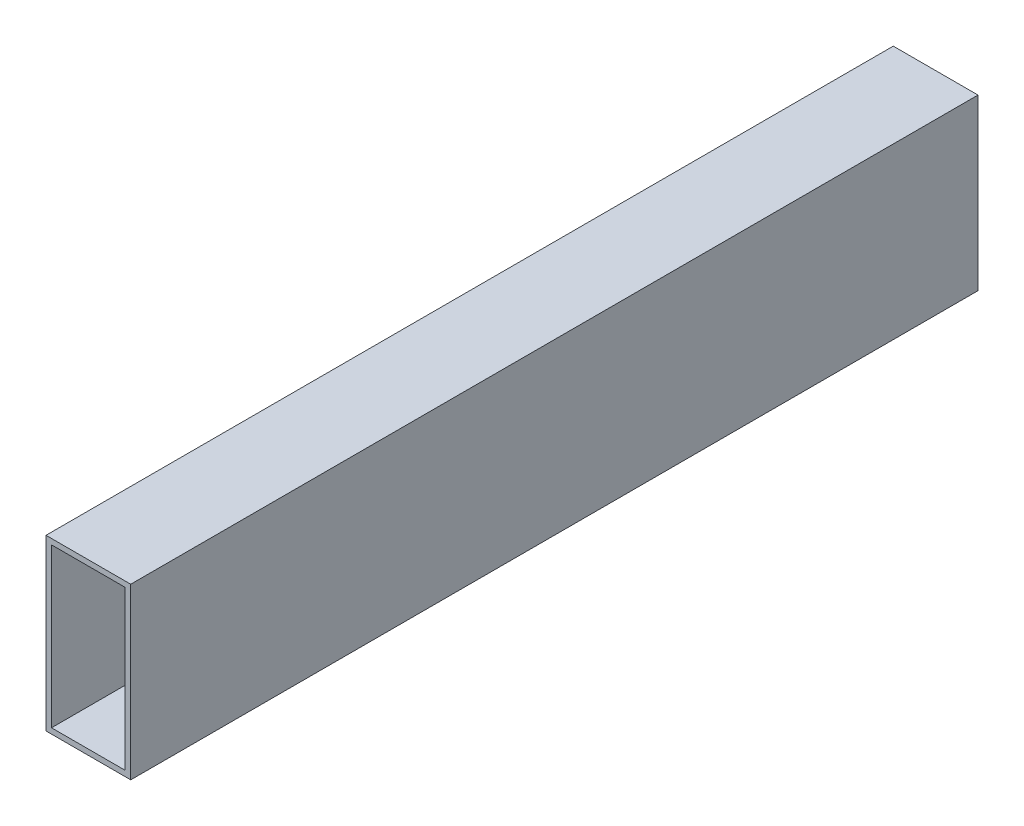
SolidWorks part; units mm, degrees
material "6061 Alloy"
ref_plane "Front Plane" through (0, 0, 0) normal (0, 0, 1) x (1, 0, 0)
ref_plane "Top Plane" through (0, 0, 0) normal (0, 1, 0) x (1, 0, 0)
ref_plane "Right Plane" through (0, 0, 0) normal (1, 0, 0) x (0, 0, -1)
sketch "Sketch1" plane through (0, 0, 0) normal (0, 0, 1) x (1, 0, 0)
  line L1 (-48.4372, -30.1994) -> (-23.0372, -30.1994)
  line L2 (-48.4372, -30.1994) -> (-48.4372, 20.6006)
  line L3 (-48.4372, 20.6006) -> (-23.0372, 20.6006)
  line L4 (-23.0372, -30.1994) -> (-23.0372, 20.6006)
  dimension "D1" = 25.4
  dimension "D2" = 50.8
extrude "Boss-Extrude1" add sketch "Sketch1" along normal blind 254
sketch "Sketch2" plane through (0, 0, 254) normal (0, 0, 1) x (1, 0, 0)
  line L0 (-48.4372, 20.6006) -> (-48.4372, -30.1994) construction
  line L1 (-46.7862, 18.9496) -> (-24.6882, 18.9496)
  line L2 (-46.7862, 18.9496) -> (-46.7862, -28.5484)
  line L3 (-46.7862, -28.5484) -> (-24.6882, -28.5484)
  line L4 (-24.6882, 18.9496) -> (-24.6882, -28.5484)
  line L5 (-46.7862, 18.9496) -> (-24.6882, -28.5484) construction
  line L6 (-46.7862, -28.5484) -> (-24.6882, 18.9496) construction
  line L7 (-23.0372, -30.1994) -> (-23.0372, 20.6006) construction
  line L8 (-23.0372, 20.6006) -> (-48.4372, 20.6006) construction
  line L9 (-48.4372, -30.1994) -> (-23.0372, -30.1994) construction
  point P0 (-35.7372, -4.7994)
  dimension "D1" = 1.651
  dimension "D2" = 1.651
  dimension "D3" = 1.651
  dimension "D4" = 1.651
extrude "Cut-Extrude1" cut sketch "Sketch2" against normal through all
